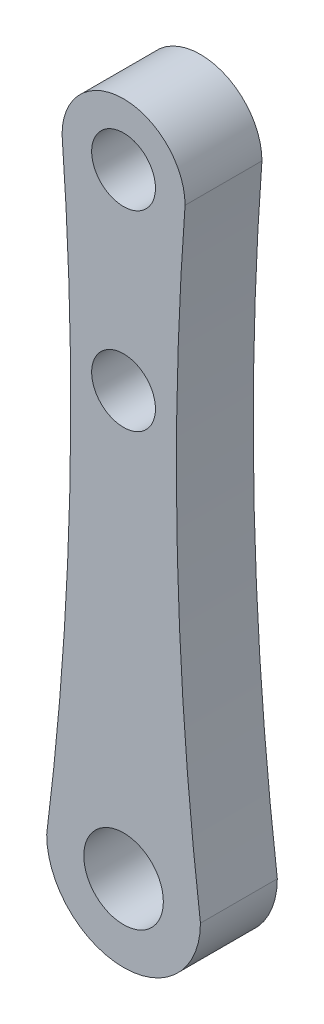
SolidWorks part; units mm, degrees
ref_plane "Plano frontal" through (0, 0, 0) normal (0, 0, 1) x (1, 0, 0)
ref_plane "Plano superior" through (0, 0, 0) normal (0, 1, 0) x (1, 0, 0)
ref_plane "Plano direito" through (0, 0, 0) normal (1, 0, 0) x (0, 0, -1)
sketch "Esboço1" plane through (0, 0, 0) normal (0, 0, 1) x (1, 0, 0)
  line L1 (208.8814, 100) -> (208.8814, 194.8851) construction
  circle A2 centre (208.8814, 155) radius 4.15
  circle A3 centre (208.8814, 179.8739) radius 4.15
  circle A4 centre (208.8814, 100) radius 5.175
  arc A17 (178.7691, 127.9998) -> (220.128, 60.4494) centre (208.8814, 100) ccw construction
  arc A18 (198.8814, 100) -> (218.8814, 100) centre (208.8814, 100) ccw
  arc A19 (216.8814, 179.8739) -> (200.8814, 179.8739) centre (208.8814, 179.8739) ccw
  arc A20 (216.8814, 179.8739) -> (218.8814, 100) centre (615.6211, 149.8961) ccw
  arc A21 (200.8814, 179.8739) -> (198.8814, 100) centre (-197.8583, 149.8961) cw
  point P22 (215.8814, 139.8869)
  point P23 (201.8814, 139.8869)
  dimension "D1" = 55
  dimension "D2" = 10.35
  dimension "D3" = 20
  dimension "D4" = 16
  dimension "D5" = 7
  dimension "D8" = 8.3
  dimension "D6" = 7
extrude "Ressalto-extrusão1" add sketch "Esboço1" along normal mid plane 10
